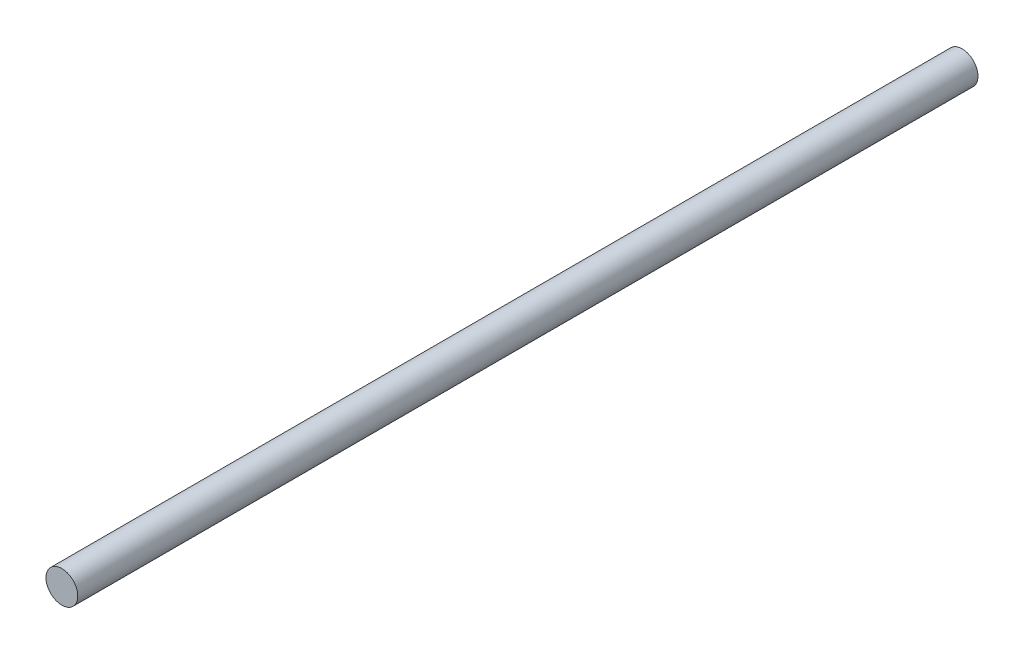
SolidWorks part; units mm, degrees
material "1060 Alloy"
ref_plane "Front Plane" through (0, 0, 0) normal (0, 0, 1) x (1, 0, 0)
ref_plane "Top Plane" through (0, 0, 0) normal (0, 1, 0) x (1, 0, 0)
ref_plane "Right Plane" through (0, 0, 0) normal (1, 0, 0) x (0, 0, -1)
sketch "Sketch1" plane through (0, 0, 0) normal (0, 0, 1) x (1, 0, 0)
  circle A0 centre (0, 0) radius 3
  dimension "D1" = 6
extrude "Boss-Extrude2" add sketch "Sketch1" along normal blind 170
